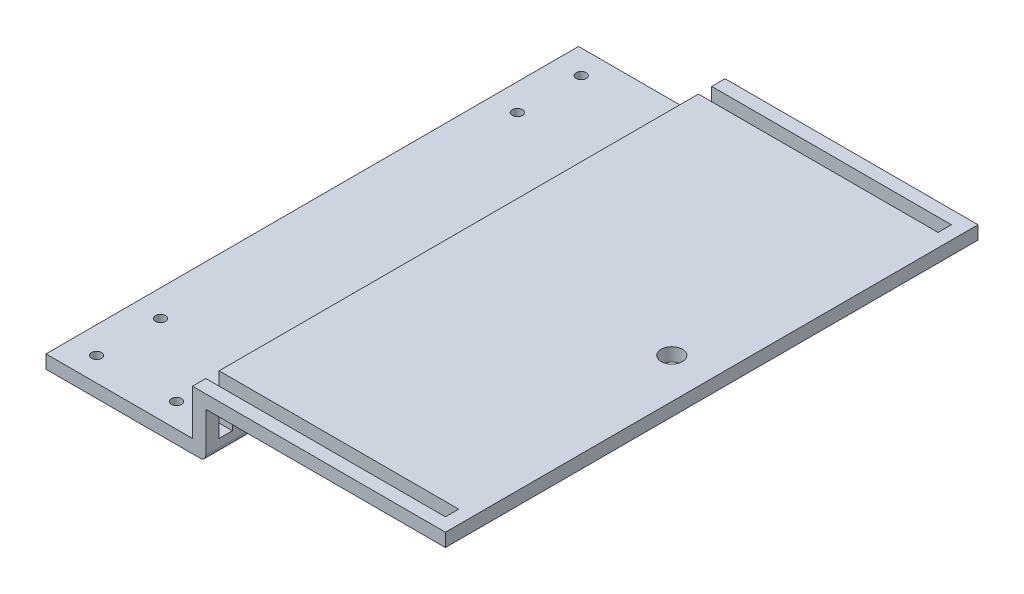
SolidWorks part; units mm, degrees
ref_plane "Front Plane" through (0, 0, 0) normal (0, 0, 1) x (1, 0, 0)
ref_plane "Top Plane" through (0, 0, 0) normal (0, 1, 0) x (1, 0, 0)
ref_plane "Right Plane" through (0, 0, 0) normal (1, 0, 0) x (0, 0, -1)
sketch "Sketch1" plane through (0, 0, 0) normal (0, 1, 0) x (1, 0, 0)
  line L1 (-75, 100) -> (75, 100)
  line L2 (-75, 100) -> (-75, -100)
  line L3 (-75, -100) -> (75, -100)
  line L4 (75, 100) -> (75, -100)
  line L5 (-75, 100) -> (75, -100) construction
  line L6 (-75, -100) -> (75, 100) construction
  point P0 (0, 0)
  dimension "D1" = 150
  dimension "D2" = 200
extrude "Boss-Extrude1" add sketch "Sketch1" along normal blind 100
shell "Shell2" thickness 5
sketch "Sketch5" plane through (0, 0, 0) normal (0, -1, 0) x (1, 0, 0)
  line L0 (-75, 100) -> (75, 100) construction
  circle A0 centre (-65, 91) radius 1.9
  circle A1 centre (-35, 91) radius 1.9
  circle A2 centre (-65, 67) radius 1.9
  circle A3 centre (-35, 67) radius 1.9
  dimension "D1" = 3.8
  dimension "D2" = 5
  dimension "D3" = 35
  dimension "D4" = 9
  dimension "D5" = 30
  dimension "D6" = 24
extrude "Cut-Extrude2" cut sketch "Sketch5" against normal blind 10
mirror "Mirror2" about plane through (0, 0, 0) normal (0, 0, 1) of "Cut-Extrude2"
sketch "Sketch6" plane through (0, 5, 0) normal (0, 1, 0) x (1, 0, 0)
  line L0 (-75, -100) -> (75, -100) construction
  line L1 (-70, 100) -> (-7.9429, 100) construction
  line L2 (-70, 100) -> (-70, -100) construction
  line L3 (-70, -100) -> (-7.9429, -100) construction
  line L4 (-7.9429, 100) -> (-7.9429, -100) construction
  line L10 (-70, -100) -> (-20, -100)
  line L11 (-70, -100) -> (-70, 100)
  line L12 (-70, 100) -> (-20, 100)
  line L13 (-20, -100) -> (-20, 100)
  dimension "D1" = 200
  dimension "D2" = 50
sketch "Sketch8" plane through (0, 0, 100) normal (0, 0, 1) x (1, 0, 0)
  line L3 (75, 17) -> (-15, 17)
  line L4 (-15, 0) -> (-15, 17)
  line L5 (75, 22) -> (-20, 22)
  line L6 (-20, 0) -> (-20, 22)
  line L8 (80, -5) -> (80, 22) construction
  line L9 (75, 0) -> (75, 17) construction
  line L10 (75, 0) -> (-15, 0) construction
  line L11 (80, -5) -> (-20, -5) construction
  line L12 (-15, 0) -> (-20, 0)
  line L13 (75, 17) -> (75, 22)
  line L14 (75, 100) -> (75, 0) construction
  line L15 (80, 22) -> (-20, 22) construction
  line L16 (-20, -5) -> (-20, 22) construction
  line L17 (-75, 0) -> (75, 0) construction
  line M3 (-75, 0) -> (75, 0)
  line M4 (75, 0) -> (75, 100)
  line M12 (70, 95) -> (70, 5)
  line M13 (70, 5) -> (-70, 5)
  dimension "D1" = 90
  dimension "D2" = 17
  dimension "D3" = 5
extrude "Boss-Extrude4" add sketch "Sketch8" against normal through all contours L6 L4 L3 L5 M13 M12 | L6 L4 M3 M13 | L5 L3 M4 M12
sketch "Sketch9" plane through (0, 0, 100) normal (0, 0, 1) x (1, 0, 0)
  line L1 (-15, 17) -> (86.1339, 17)
  line L2 (-15, 17) -> (-15, -14.9961)
  line L3 (-15, -14.9961) -> (86.1339, -14.9961)
  line L4 (86.1339, 17) -> (86.1339, -14.9961)
extrude "Cut-Extrude4" cut sketch "Sketch9" against normal through all
sketch "Sketch10" plane through (0, 17, 0) normal (0, -1, 0) x (1, 0, 0)
  line L0 (75, 100) -> (75, -100) construction
  circle A0 centre (60, 0) radius 4
  dimension "D1" = 8
  dimension "D2" = 15
extrude "Cut-Extrude5" cut sketch "Sketch10" against normal blind 10
sketch "Sketch11" plane through (0, 100, 0) normal (0, 1, 0) x (1, 0, 0)
  line L0 (-75, -100) -> (75, -100) construction
  line L1 (70, -95) -> (-70, -95)
  line L2 (70, -95) -> (70, -90)
  line L3 (70, -90) -> (-70, -90)
  line L4 (-70, -95) -> (-70, -90)
  line L5 (75, -100) -> (75, 100) construction
  line L6 (-75, 100) -> (-75, -100) construction
  point P6 (70, -92.5)
  dimension "D1" = 5
  dimension "D2" = 5
  dimension "D3" = 5
  dimension "D4" = 5
extrude "Cut-Extrude7" cut sketch "Sketch11" against normal up to surface (95 mm away) contours L4 L1 L2 L3 up to face at (-35, 5, -89.1)
mirror "Mirror3" about plane through (0, 0, 0) normal (0, 0, 1) of "Cut-Extrude7"
sketch "Sketch15" plane through (0, 100, 0) normal (0, 1, 0) x (1, 0, 0)
  circle A0 centre (50, 28) radius 1.2
  circle A1 centre (50, -28) radius 1.2
  circle A2 centre (-20, 20) radius 1.2
  circle A3 centre (-20, -20) radius 1.2
  dimension "D1" = 2.4
  dimension "D2" = 56
  dimension "D3" = 28
  dimension "D4" = 40
  dimension "D5" = 20
  dimension "D6" = 70
  dimension "D7" = 50
extrude "Cut-Extrude11" cut sketch "Sketch15" against normal blind 10
sketch "Sketch36" plane through (70, 0, 0) normal (-1, 0, 0) x (0, 0, 1)
  line L1 (-43.2021, 65) -> (16.7979, 65)
  line L2 (-43.2021, 65) -> (-43.2021, 60)
  line L3 (-43.2021, 60) -> (16.7979, 60)
  line L4 (16.7979, 65) -> (16.7979, 60)
  line L5 (-100, 0) -> (100, 0) construction
  point P6 (16.7979, 62.5)
  dimension "D1" = 65
  dimension "D2" = 5
  dimension "D3" = 16.7979
  dimension "D4" = 60
extrude "Boss-Extrude7" add sketch "Sketch36" along normal blind 10
mirror "Mirror5" about plane through (0, 0, 0) normal (1, 0, 0) of "Boss-Extrude7"
sketch "Sketch37" plane through (75, 0, 0) normal (1, 0, 0) x (0, 0, -1)
  circle A0 centre (0, 75) radius 3.5
  dimension "D1" = 7
  dimension "D2" = 75
extrude "Cut-Extrude15" cut sketch "Sketch37" against normal blind 60
sketch "Sketch38" plane through (-75, 0, 0) normal (-1, 0, 0) x (0, 0, 1)
  circle A0 centre (0, 80) radius 5
  dimension "D1" = 10
  dimension "D2" = 80
extrude "Cut-Extrude16" cut sketch "Sketch38" against normal blind 70
sketch "Sketch40" plane through (0, 0, 100) normal (0, 0, 1) x (1, 0, 0)
  line L1 (80.0665, 22) -> (-99.0991, 22)
  line L2 (80.0665, 22) -> (80.0665, 107.1352)
  line L3 (80.0665, 107.1352) -> (-99.0991, 107.1352)
  line L4 (-99.0991, 22) -> (-99.0991, 107.1352)
  line L5 (-20, 5) -> (-107.942, 5)
  line L6 (-20, 5) -> (-20, 22)
  line L7 (-20, 22) -> (-107.942, 22)
  line L8 (-107.942, 5) -> (-107.942, 22)
  line M1 (-20, 22) -> (-20, 5)
  line M2 (-20, 5) -> (-70, 5)
  line M3 (-70, 5) -> (-70, 95)
  line M4 (-70, 95) -> (70, 95)
  line M5 (70, 95) -> (70, 22)
  line M6 (70, 22) -> (-20, 22)
extrude "Cut-Extrude18" cut sketch "Sketch40" against normal through all contours L1 M6 M5 M4 M3 | L1 M1 M3 M2 | L6 L5 L8 L7
fillet "Fillet1" radius 2 3 edges at (-15, 17, 0) (-15, 0, 0) (-20, 5, 0)
